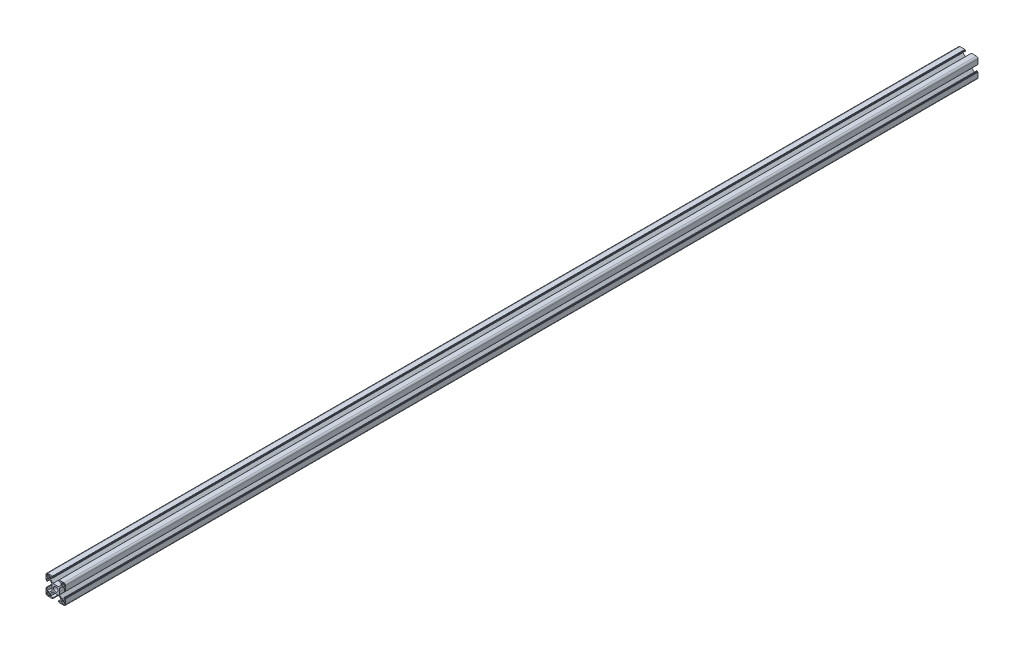
SolidWorks part; units mm, degrees
material "6061-T6 (SS)"
ref_plane "前视基准面" through (0, 0, 0) normal (0, 0, 1) x (1, 0, 0)
ref_plane "上视基准面" through (0, 0, 0) normal (0, 1, 0) x (1, 0, 0)
ref_plane "右视基准面" through (0, 0, 0) normal (1, 0, 0) x (0, 0, -1)
sketch "Sketch1" plane through (0, 0, 0) normal (0, 0, 1) x (1, 0, 0)
  line L0 (-5.1, 15) -> (-5.1, 14.2)
  line L1 (-12.5, -15) -> (12.5, -15)
  line L2 (-15, -12.5) -> (-15, 12.5)
  line L3 (-12.5, 15) -> (12.5, 15)
  line L4 (15, -12.5) -> (15, 12.5)
  line L5 (-15, -15) -> (15, 15) construction
  line L6 (-15, 15) -> (15, -15) construction
  line L7 (-5.1, 14.2) -> (-4.1, 14.2)
  line L8 (-4.1, 14.2) -> (-4.1, 13.2)
  line L9 (-4.1, 13.2) -> (-8.25, 13.2)
  line L10 (-8.25, 13.2) -> (-8.25, 9.5228)
  line L11 (-8.25, 9.5228) -> (-4.4272, 5.7)
  line L12 (-4.4272, 5.7) -> (4.4272, 5.7)
  line L13 (-5.1, 15) -> (5.1, 15)
  line L14 (0, 15) -> (0, 5.7) construction
  line L15 (8.25, 9.5228) -> (4.4272, 5.7)
  line L16 (8.25, 13.2) -> (8.25, 9.5228)
  line L17 (4.1, 13.2) -> (8.25, 13.2)
  line L18 (4.1, 14.2) -> (4.1, 13.2)
  line L19 (5.1, 14.2) -> (4.1, 14.2)
  line L20 (5.1, 15) -> (5.1, 14.2)
  line L21 (15, 5.1) -> (14.2, 5.1)
  line L22 (14.2, 5.1) -> (14.2, 4.1)
  line L23 (14.2, 4.1) -> (13.2, 4.1)
  line L24 (13.2, 4.1) -> (13.2, 8.25)
  line L25 (13.2, 8.25) -> (9.5228, 8.25)
  line L26 (9.5228, 8.25) -> (5.7, 4.4272)
  line L27 (5.7, 4.4272) -> (5.7, -4.4272)
  line L28 (15, 5.1) -> (15, -5.1)
  line L29 (9.5228, -8.25) -> (5.7, -4.4272)
  line L30 (13.2, -8.25) -> (9.5228, -8.25)
  line L31 (13.2, -4.1) -> (13.2, -8.25)
  line L32 (14.2, -4.1) -> (13.2, -4.1)
  line L33 (14.2, -5.1) -> (14.2, -4.1)
  line L34 (15, -5.1) -> (14.2, -5.1)
  line L35 (15, 0) -> (5.7, 0) construction
  line L36 (5.1, -15) -> (5.1, -14.2)
  line L37 (5.1, -14.2) -> (4.1, -14.2)
  line L38 (4.1, -14.2) -> (4.1, -13.2)
  line L39 (4.1, -13.2) -> (8.25, -13.2)
  line L40 (8.25, -13.2) -> (8.25, -9.5228)
  line L41 (8.25, -9.5228) -> (4.4272, -5.7)
  line L42 (4.4272, -5.7) -> (-4.4272, -5.7)
  line L43 (5.1, -15) -> (-5.1, -15)
  line L44 (-8.25, -9.5228) -> (-4.4272, -5.7)
  line L45 (-8.25, -13.2) -> (-8.25, -9.5228)
  line L46 (-4.1, -13.2) -> (-8.25, -13.2)
  line L47 (-4.1, -14.2) -> (-4.1, -13.2)
  line L48 (-5.1, -14.2) -> (-4.1, -14.2)
  line L49 (-5.1, -15) -> (-5.1, -14.2)
  line L50 (0, -15) -> (0, -5.7) construction
  line L51 (-15, -5.1) -> (-14.2, -5.1)
  line L52 (-14.2, -5.1) -> (-14.2, -4.1)
  line L53 (-14.2, -4.1) -> (-13.2, -4.1)
  line L54 (-13.2, -4.1) -> (-13.2, -8.25)
  line L55 (-13.2, -8.25) -> (-9.5228, -8.25)
  line L56 (-9.5228, -8.25) -> (-5.7, -4.4272)
  line L57 (-5.7, -4.4272) -> (-5.7, 4.4272)
  line L58 (-15, -5.1) -> (-15, 5.1)
  line L59 (-9.5228, 8.25) -> (-5.7, 4.4272)
  line L60 (-13.2, 8.25) -> (-9.5228, 8.25)
  line L61 (-13.2, 4.1) -> (-13.2, 8.25)
  line L62 (-14.2, 4.1) -> (-13.2, 4.1)
  line L63 (-14.2, 5.1) -> (-14.2, 4.1)
  line L64 (-15, 5.1) -> (-14.2, 5.1)
  line L65 (-15, 0) -> (-5.7, 0) construction
  line L66 (0, 0) -> (0, 5.7) construction
  circle A0 centre (0, 0) radius 3.4
  arc A1 (-12.5, -15) -> (-15, -12.5) centre (-12.5, -12.5) cw
  arc A2 (12.5, -15) -> (15, -12.5) centre (12.5, -12.5) ccw
  arc A3 (12.5, 15) -> (15, 12.5) centre (12.5, 12.5) cw
  arc A4 (-15, 12.5) -> (-12.5, 15) centre (-12.5, 12.5) cw
  point P0 (0, 0)
  dimension "D3" = 6.8
  dimension "D12" = 2.5
  dimension "D1" = 30
  dimension "D2" = 30
  dimension "D4" = 16.5
  dimension "D5" = 8.2
  dimension "D6" = 10.2
  dimension "D7" = 7.5
  dimension "D9" = 1.8
  dimension "D10" = 1.8
  dimension "D11" = 0.8
  dimension "D8" = 4
extrude "Extrude1" add sketch "Sketch1" along normal blind 1400 contours A4 L2 L64 L63 L62 L61 L60 L59 L57 L56 L55 L54 L53 L52 L51 A1 L1 L49 L48 L47 L46 L45 L44 L42 L41 L40 L39 L38 L37 L36 A2 L4 L34 L33 L32 L31 L30 L29 L27 L26 L25 L24 L23 L22 L21 A3 L3 L20
sketch "Sketch2" plane through (0, 0, 1400) normal (0, 0, 1) x (1, 0, 0)
  line L0 (13.7, 12.7) -> (13.7, 10.55)
  line L1 (-12.7, 13.7) -> (-10.55, 13.7)
  line L2 (-13.7, 12.7) -> (-13.7, 10.55)
  line L3 (-12.7, 9.55) -> (-10.55, 9.55)
  line L4 (-9.55, 12.7) -> (-9.55, 10.55)
  line L5 (-13.7, 13.7) -> (-9.55, 9.55) construction
  line L6 (-13.7, 9.55) -> (-9.55, 13.7) construction
  line L7 (12.7, 13.7) -> (10.55, 13.7)
  line L8 (9.55, 12.7) -> (9.55, 10.55)
  line L9 (12.7, 9.55) -> (10.55, 9.55)
  line L10 (12.7, -13.7) -> (10.55, -13.7)
  line L11 (13.7, -12.7) -> (13.7, -10.55)
  line L12 (12.7, -9.55) -> (10.55, -9.55)
  line L13 (9.55, -12.7) -> (9.55, -10.55)
  line L14 (-13.7, -12.7) -> (-13.7, -10.55)
  line L15 (-12.7, -13.7) -> (-10.55, -13.7)
  line L16 (-9.55, -12.7) -> (-9.55, -10.55)
  line L17 (-12.7, -9.55) -> (-10.55, -9.55)
  line L18 (0, 0) -> (-9.55, 9.55) construction
  line L19 (-12.5, 15) -> (-5.1, 15) construction
  line L20 (-15, 5.1) -> (-15, 12.5) construction
  line L21 (-13.2, 8.25) -> (-9.5228, 8.25) construction
  line L22 (-8.25, 13.2) -> (-8.25, 9.5228) construction
  arc A0 (-13.7, -12.7) -> (-12.7, -13.7) centre (-12.7, -12.7) ccw
  arc A1 (-10.55, -13.7) -> (-9.55, -12.7) centre (-10.55, -12.7) ccw
  arc A2 (-9.55, -10.55) -> (-10.55, -9.55) centre (-10.55, -10.55) ccw
  arc A3 (-13.7, -10.55) -> (-12.7, -9.55) centre (-12.7, -10.55) cw
  arc A4 (13.7, -10.55) -> (12.7, -9.55) centre (12.7, -10.55) ccw
  arc A5 (12.7, -13.7) -> (13.7, -12.7) centre (12.7, -12.7) ccw
  arc A6 (10.55, -13.7) -> (9.55, -12.7) centre (10.55, -12.7) cw
  arc A7 (10.55, -9.55) -> (9.55, -10.55) centre (10.55, -10.55) ccw
  arc A8 (13.7, 12.7) -> (12.7, 13.7) centre (12.7, 12.7) ccw
  arc A9 (13.7, 10.55) -> (12.7, 9.55) centre (12.7, 10.55) cw
  arc A10 (9.55, 10.55) -> (10.55, 9.55) centre (10.55, 10.55) ccw
  arc A11 (10.55, 13.7) -> (9.55, 12.7) centre (10.55, 12.7) ccw
  arc A12 (-10.55, 13.7) -> (-9.55, 12.7) centre (-10.55, 12.7) cw
  arc A13 (-10.55, 9.55) -> (-9.55, 10.55) centre (-10.55, 10.55) ccw
  arc A14 (-13.7, 10.55) -> (-12.7, 9.55) centre (-12.7, 10.55) ccw
  arc A15 (-12.7, 13.7) -> (-13.7, 12.7) centre (-12.7, 12.7) ccw
  point P0 (-11.625, 11.625)
  dimension "D2" = 1
  dimension "D3" = 1.3
  dimension "D4" = 1.3
  dimension "D5" = 1.3
  dimension "D6" = 1.3
  dimension "D1" = 4
extrude "Extrude2" cut sketch "Sketch2" against normal through all
